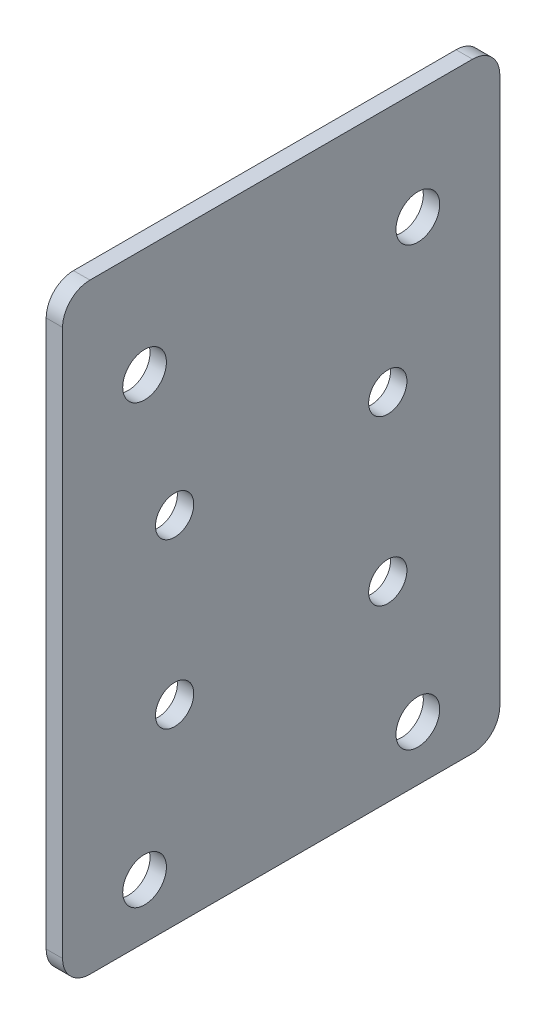
SolidWorks part; units mm, degrees
ref_plane "Front" through (0, 0, 0) normal (0, 0, 1) x (1, 0, 0)
ref_plane "Top" through (0, 0, 0) normal (0, 1, 0) x (1, 0, 0)
ref_plane "Right" through (0, 0, 0) normal (1, 0, 0) x (0, 0, -1)
sketch "Sketch1" plane through (0, 0, 0) normal (0, 0, 1) x (1, 0, 0)
  line L0 (0, -23.2805) -> (0, 86.7195)
  line L2 (3, -23.2805) -> (3, 83.7195)
  line L5 (0, -23.2805) -> (3, -23.2805)
  line L6 (0, 86.7195) -> (37, 86.7195) construction
  line L7 (3, 83.7195) -> (37, 83.7195) construction
  line L8 (0, 86.7195) -> (3, 86.7195)
  line L9 (3, 86.7195) -> (3, 83.7195)
  dimension "D2" = 110
  dimension "D1" = 3
extrude "Boss-Extrude1" add sketch "Sketch1" along normal mid plane 80
sketch "Sketch16" plane through (3, 0, 0) normal (1, 0, 0) x (0, 0, -1)
  line L1 (-40, 86.7195) -> (40, 86.7195) construction
  circle A0 centre (-19.5, 11.7195) radius 3.5
  circle A1 centre (19.5, 11.7195) radius 3.5
  circle A2 centre (19.5, 41.7195) radius 3.5
  circle A3 centre (-19.5, 41.7195) radius 3.5
  point P8 (0, 0)
  point P12 (0, 0)
  dimension "D7" = 7
  dimension "D8" = 7
  dimension "D9" = 7
  dimension "D10" = 7
  dimension "D1" = 39
  dimension "D2" = 39
  dimension "D3" = 19.5
  dimension "D4" = 19.5
  dimension "D5" = 30
  dimension "D6" = 45
  dimension "D11" = 45
  dimension "D12" = 0
extrude "Cut-Extrude5" cut sketch "Sketch16" against normal through all
sketch "Sketch17" plane through (0, 0, 0) normal (-1, 0, 0) x (0, 0, 1)
  line L6 (40, 86.7195) -> (-40, 86.7195) construction
  circle A4 centre (-25, 66.7195) radius 4
  circle A5 centre (24.9975, 66.7195) radius 4
  circle A6 centre (-25, -13.2805) radius 4
  circle A7 centre (24.9975, -13.2805) radius 4
  point P1 (0, 0)
  point P5 (32.9567, -5.1227)
  point P13 (0, 0)
  point P14 (0, 0)
  point P16 (-23.879, 0.0592)
  dimension "D7" = 8
  dimension "D8" = 8
  dimension "D9" = 80
  dimension "D10" = 20
  dimension "D2" = 25
  dimension "D3" = 8
  dimension "D4" = 8
  dimension "D1" = 49.9975
  dimension "D5" = 49.9975
  dimension "D6" = 25
  dimension "D11" = 80
  dimension "D12" = 20
extrude "Cut-Extrude7" cut sketch "Sketch17" against normal through all
fillet "Fillet1" radius 5 4 edges at (1.5, -23.2805, 40) (1.5, -23.2805, -40) (1.5, 86.7195, -40) (1.5, 86.7195, 40)
